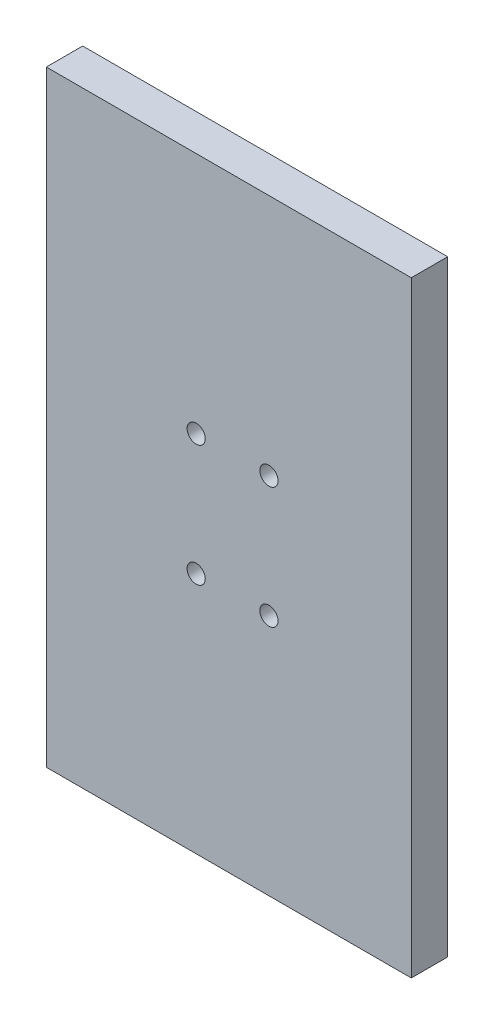
SolidWorks part; units mm, degrees
ref_plane "Alzado" through (0, 0, 0) normal (0, 0, 1) x (1, 0, 0)
ref_plane "Planta" through (0, 0, 0) normal (0, 1, 0) x (1, 0, 0)
ref_plane "Vista lateral" through (0, 0, 0) normal (1, 0, 0) x (0, 0, -1)
sketch "Croquis1" plane through (0, 0, 0) normal (0, 0, 1) x (1, 0, 0)
  line L0 (58.9459, -92.8855) -> (-61.4193, -92.8855)
  line L1 (58.9459, -92.8855) -> (58.9459, 107.1145)
  line L2 (58.9459, 107.1145) -> (-61.4193, 107.1145)
  line L3 (-61.4193, -92.8855) -> (-61.4193, 107.1145)
  dimension "D1" = 200
  dimension "D2" = 120.3651
extrude "Saliente-Extruir1" add sketch "Croquis1" along normal blind 12
sketch "Croquis2" plane through (0, 0, 12) normal (0, 0, 1) x (1, 0, 0)
  line L0 (0, 146.1692) -> (0, -146.1692) construction
  line L1 (81.5761, 107.1145) -> (81.5761, 27.1145) construction
  line L4 (81.5761, 27.1145) -> (81.5761, -12.8855) construction
  line L5 (81.5761, -12.8855) -> (81.5761, -92.8855) construction
  line L6 (58.9459, 107.1145) -> (-61.4193, 107.1145) construction
  circle A0 centre (-12, 27.1145) radius 3
  circle A1 centre (12, 27.1145) radius 3
  circle A2 centre (-12, -12.8855) radius 3
  circle A3 centre (12, -12.8855) radius 3
  point P12 (0, 0)
  point P18 (0, 0)
  dimension "D1" = 6
  dimension "D2" = 40
  dimension "D3" = 24
extrude "Cortar-Extruir1" cut sketch "Croquis2" against normal up to next
